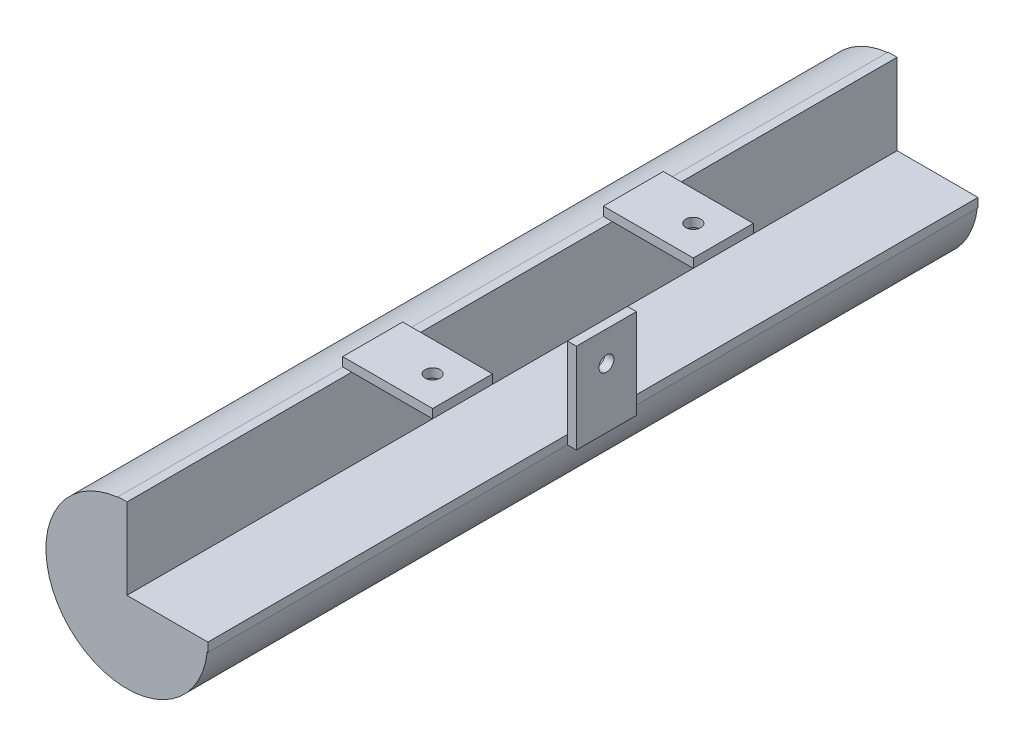
SolidWorks part; units mm, degrees
ref_plane "Front Plane" through (0, 0, 0) normal (0, 0, 1) x (1, 0, 0)
ref_plane "Top Plane" through (0, 0, 0) normal (0, 1, 0) x (1, 0, 0)
ref_plane "Right Plane" through (0, 0, 0) normal (1, 0, 0) x (0, 0, -1)
sketch "Sketch4" plane through (0, 0, 0) normal (0, 0, 1) x (1, 0, 0)
  line L0 (0, 0) -> (27, 0)
  line L5 (0, 27) -> (0, 0)
  line L6 (0, 27) -> (-3, 27)
  line L7 (-3, 27) -> (-3, 26.8328)
  line L8 (27, 0) -> (27, -3)
  line L9 (27, -3) -> (26.8001, -3)
  arc A1 (-3, 26.8328) -> (26.8001, -3) centre (-0.0331, -0.0037) ccw
  dimension "D3" = 27
  dimension "D1" = 27
  dimension "D2" = 27
  dimension "D4" = 3
  dimension "D5" = 3
  dimension "D6" = 0.1672
  dimension "D7" = 0.1999
extrude "Boss-Extrude1" add sketch "Sketch4" along normal mid plane 257
sketch "Sketch7" plane through (0, 27, 0) normal (0, 1, 0) x (1, 0, 0)
  line L0 (-3, -128.5) -> (-3, 128.5) construction
  line L1 (-3, -53.5) -> (27, -53.5)
  line L2 (-3, -53.5) -> (-3, -33.5)
  line L3 (-3, -33.5) -> (27, -33.5)
  line L4 (27, -53.5) -> (27, -33.5)
  line L5 (27, -128.5) -> (0, -128.5) construction
  line L6 (-3, -128.5) -> (-3, 128.5) construction
  line L7 (-3, 33.5) -> (27, 33.5)
  line L8 (-3, 33.5) -> (-3, 53.5)
  line L9 (-3, 53.5) -> (27, 53.5)
  line L10 (27, 33.5) -> (27, 53.5)
  line L11 (27, 128.5) -> (0, 128.5) construction
  dimension "D1" = 20
  dimension "D2" = 30
  dimension "D3" = 75
  dimension "D4" = 20
  dimension "D5" = 30
  dimension "D6" = 75
extrude "Boss-Extrude4" add sketch "Sketch7" along normal blind 3
sketch "Sketch9" plane through (0, 30, 0) normal (0, 1, 0) x (1, 0, 0)
  line L0 (27, 33.5) -> (27, 53.5) construction
  line L1 (-3, 33.5) -> (27, 33.5) construction
  line L2 (27, -33.5) -> (-3, -33.5) construction
  line L3 (27, -53.5) -> (27, -33.5) construction
  circle A0 centre (17, -43.5) radius 2.5
  circle A1 centre (17, 43.5) radius 2.5
  dimension "D1" = 5
  dimension "D2" = 5
  dimension "D3" = 10
  dimension "D4" = 10
  dimension "D5" = 10
  dimension "D6" = 10
extrude "Cut-Extrude1" cut sketch "Sketch9" against normal up to next
sketch "Sketch10" plane through (27, 0, 0) normal (1, 0, 0) x (0, 0, -1)
  line L0 (-128.5, -3) -> (128.5, -3) construction
  line L1 (11.5, -3) -> (-8.5, -3)
  line L2 (11.5, -3) -> (11.5, 27)
  line L3 (11.5, 27) -> (-8.5, 27)
  line L4 (-8.5, -3) -> (-8.5, 27)
  line L5 (-128.5, 0) -> (-128.5, 27) construction
  dimension "D1" = 30
  dimension "D2" = 20
  dimension "D3" = 120
extrude "Boss-Extrude5" add sketch "Sketch10" along normal blind 3
sketch "Sketch11" plane through (30, 0, 0) normal (1, 0, 0) x (0, 0, -1)
  line L0 (11.5, -3) -> (11.5, 27) construction
  line L1 (11.5, 27) -> (-8.5, 27) construction
  circle A0 centre (1.5, 17) radius 2.5
  dimension "D1" = 5
  dimension "D2" = 10
  dimension "D3" = 10
extrude "Cut-Extrude2" cut sketch "Sketch11" against normal up to next
